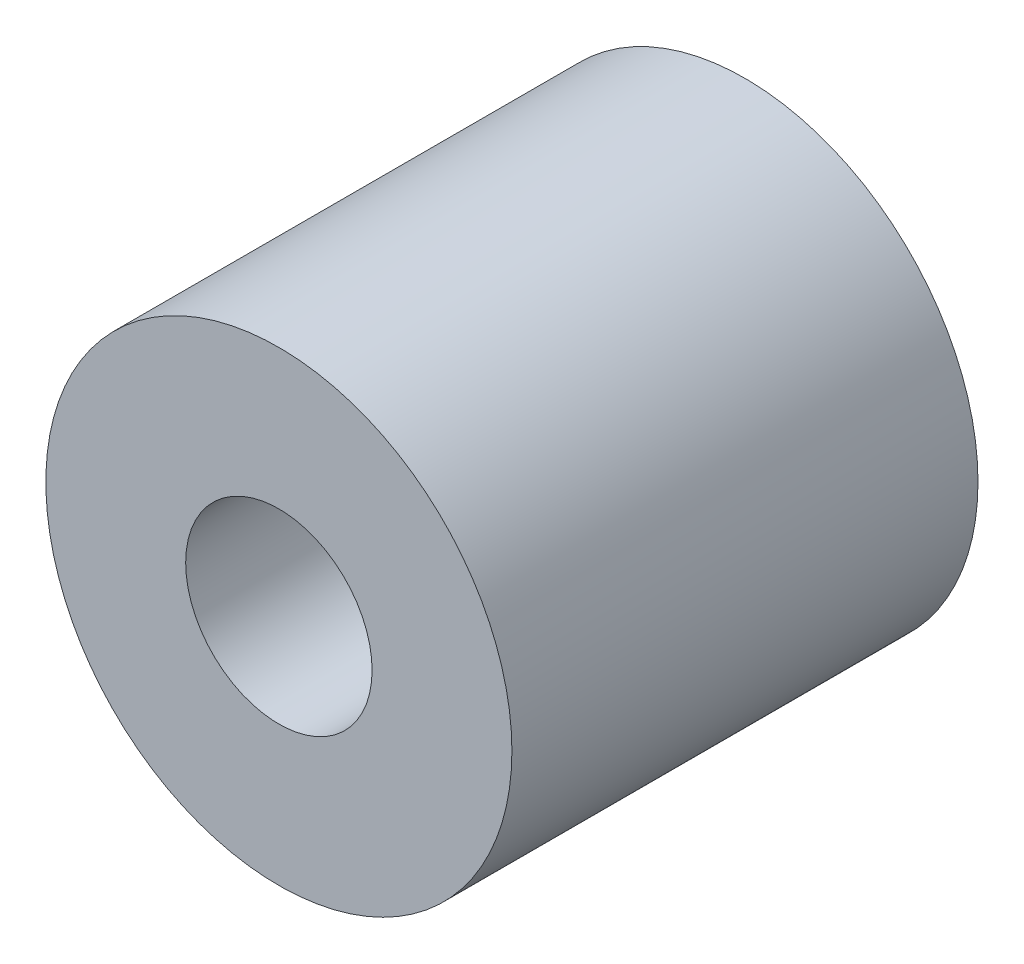
SolidWorks part; units mm, degrees
material "ABS"
ref_plane "Front Plane" through (0, 0, 0) normal (0, 0, 1) x (1, 0, 0)
ref_plane "Top Plane" through (0, 0, 0) normal (0, 1, 0) x (1, 0, 0)
ref_plane "Right Plane" through (0, 0, 0) normal (1, 0, 0) x (0, 0, -1)
sketch "Sketch1" plane through (0, 0, 0) normal (0, 0, 1) x (1, 0, 0)
  circle A0 centre (0, 0) radius 2.5
  circle A1 centre (0, 0) radius 1
  dimension "D1" = 5
  dimension "D2" = 2
extrude "Boss-Extrude1" add sketch "Sketch1" along normal blind 5
